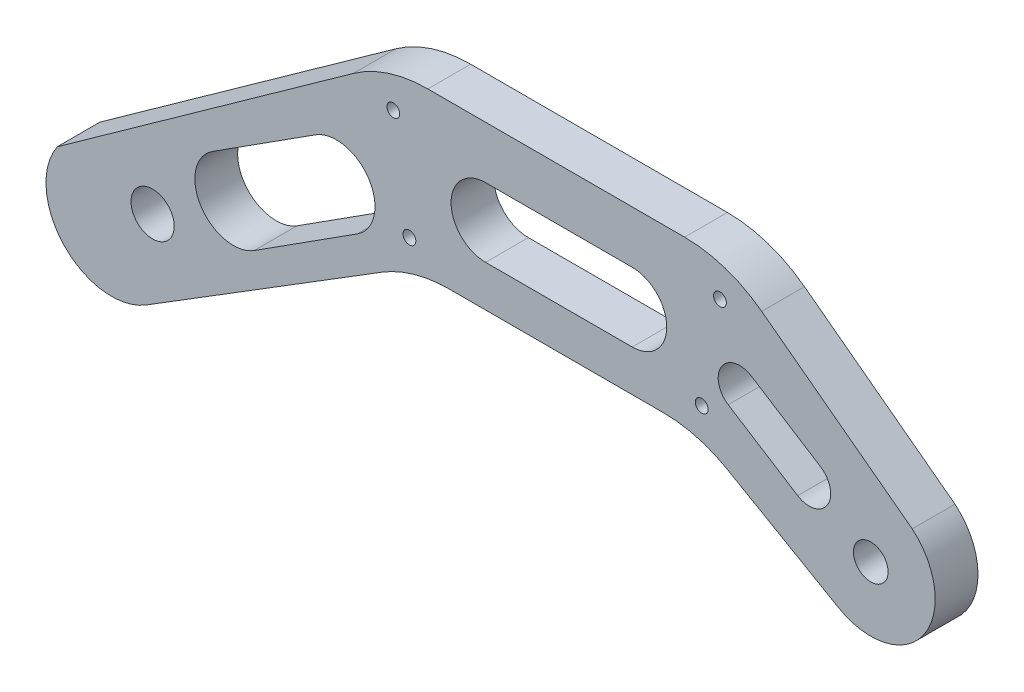
SolidWorks part; units mm, degrees
ref_plane "Front Plane" through (0, 0, 0) normal (0, 0, 1) x (1, 0, 0)
ref_plane "Top Plane" through (0, 0, 0) normal (0, 1, 0) x (1, 0, 0)
ref_plane "Right Plane" through (0, 0, 0) normal (1, 0, 0) x (0, 0, -1)
sketch "Sketch1" plane through (0, 0, 0) normal (0, 0, 1) x (1, 0, 0)
  line L0 (-36.5059, 38) -> (23.4941, 38)
  line L1 (41.5151, 31.9842) -> (76.6804, 5.5622)
  line L2 (-31.5059, 0) -> (18.4941, 0)
  line L3 (33.4898, -4.0167) -> (59.4731, -19.0124)
  line L4 (-53.9471, 32.4091) -> (-123.1061, -17.0079)
  line L5 (-47.3246, -4.5095) -> (-102.3151, -38.6351)
  line L6 (99.3935, 38) -> (45.1336, -39.4912) construction
  line L7 (-112.4053, 38) -> (99.3935, 38) construction
  line L8 (-112.4053, 38) -> (-112.4053, -39.4912) construction
  line L9 (-112.4053, -39.4912) -> (99.3935, -39.4912) construction
  line L10 (99.3935, 38) -> (99.3935, -39.4912) construction
  line L11 (-81.9332, -7.3905) -> (-57.8747, 8) construction
  line L12 (-6.5059, 38) -> (-6.5059, -39.4912) construction
  line L13 (-45.6636, 36.5681) -> (-39.7303, -1.1494) construction
  line L14 (32.9934, 36.4563) -> (26.2563, -1.0216) construction
  line L15 (66.9996, -5.9709) -> (29.6249, 17.7174) construction
  line L16 (29.6249, 17.7174) -> (-42.697, 17.7094) construction
  line L17 (-110.4027, -25.6027) -> (-42.697, 17.7094) construction
  line L18 (-86.7939, 0.2077) -> (-62.7353, 15.5982)
  line L19 (-77.0726, -14.9887) -> (-53.014, 0.4018)
  line L22 (-114.6339, -16.4384) -> (-115.3599, -16.9028) construction
  line L24 (-23.0158, 17.7115) -> (11.2516, 17.7153) construction
  line L25 (-23.0167, 25.7773) -> (11.2507, 25.7811)
  line L26 (-23.0149, 9.6458) -> (11.2525, 9.6496)
  line L27 (36.3755, 13.4388) -> (52.6086, 3.1502) construction
  line L28 (39.069, 17.6886) -> (55.3022, 7.4)
  line L29 (33.6819, 9.189) -> (49.9151, -1.0997)
  arc A0 (33.4898, -4.0167) -> (18.4941, 0) centre (18.4941, -30) ccw
  arc A1 (41.5151, 31.9842) -> (23.4941, 38) centre (23.4941, 8) ccw
  arc A2 (-36.5059, 38) -> (-53.9471, 32.4091) centre (-36.5059, 8) ccw
  arc A3 (-31.5059, 0) -> (-47.3246, -4.5095) centre (-31.5059, -30) ccw
  arc A4 (59.4731, -19.0124) -> (76.6804, 5.5622) centre (66.9996, -5.9709) ccw
  arc A5 (-102.3151, -38.6351) -> (-123.1061, -17.0079) centre (-110.4027, -25.6027) cw
  circle A6 centre (66.9996, -5.9709) radius 4.05
  circle A7 centre (-44.5758, 29.6531) radius 1.5
  arc A8 (-86.7939, 0.2077) -> (-77.0726, -14.9887) centre (-81.9332, -7.3905) ccw
  arc A9 (-53.014, 0.4018) -> (-62.7353, 15.5982) centre (-57.8747, 8) ccw
  circle A12 centre (-40.8181, 5.7656) radius 1.5
  circle A13 centre (31.7549, 29.5668) radius 1.5
  circle A14 centre (27.4948, 5.868) radius 1.5
  arc A15 (-23.0167, 25.7773) -> (-23.0149, 9.6458) centre (-23.0158, 17.7115) ccw
  arc A16 (11.2525, 9.6496) -> (11.2507, 25.7811) centre (11.2516, 17.7153) ccw
  arc A17 (39.069, 17.6886) -> (33.6819, 9.189) centre (36.3755, 13.4388) ccw
  arc A18 (49.9151, -1.0997) -> (55.3022, 7.4) centre (52.6086, 3.1502) ccw
  circle A19 centre (-100.8213, -19.4734) radius 5.05
  point P13 (-6.0432, -4.9781)
  point P22 (33.5087, 38)
  point P38 (-69.904, 0.3047)
  point P62 (-5.8821, 17.7134)
  point P69 (44.4921, 8.2945)
  dimension "D1" = 38
  dimension "D4" = 30
  dimension "D6" = 30
  dimension "D3" = 30
  dimension "D5" = 30
  dimension "D20" = 8.1
  dimension "D22" = 3
  dimension "D21" = 3
  dimension "D27" = 3
  dimension "D28" = 3
  dimension "D15" = 10.1
  dimension "D2" = 54
  dimension "D7" = 30
  dimension "D8" = 30
  dimension "D9" = 55
  dimension "D10" = 85
  dimension "D11" = 25
  dimension "D12" = 30
  dimension "D13" = 25
  dimension "D14" = 25
  dimension "D16" = 30
  dimension "D17" = 69
  dimension "D29" = 7
  dimension "D30" = 7
  dimension "D31" = 7
  dimension "D32" = 7
extrude "Boss-Extrude1" add sketch "Sketch1" along normal blind 10
